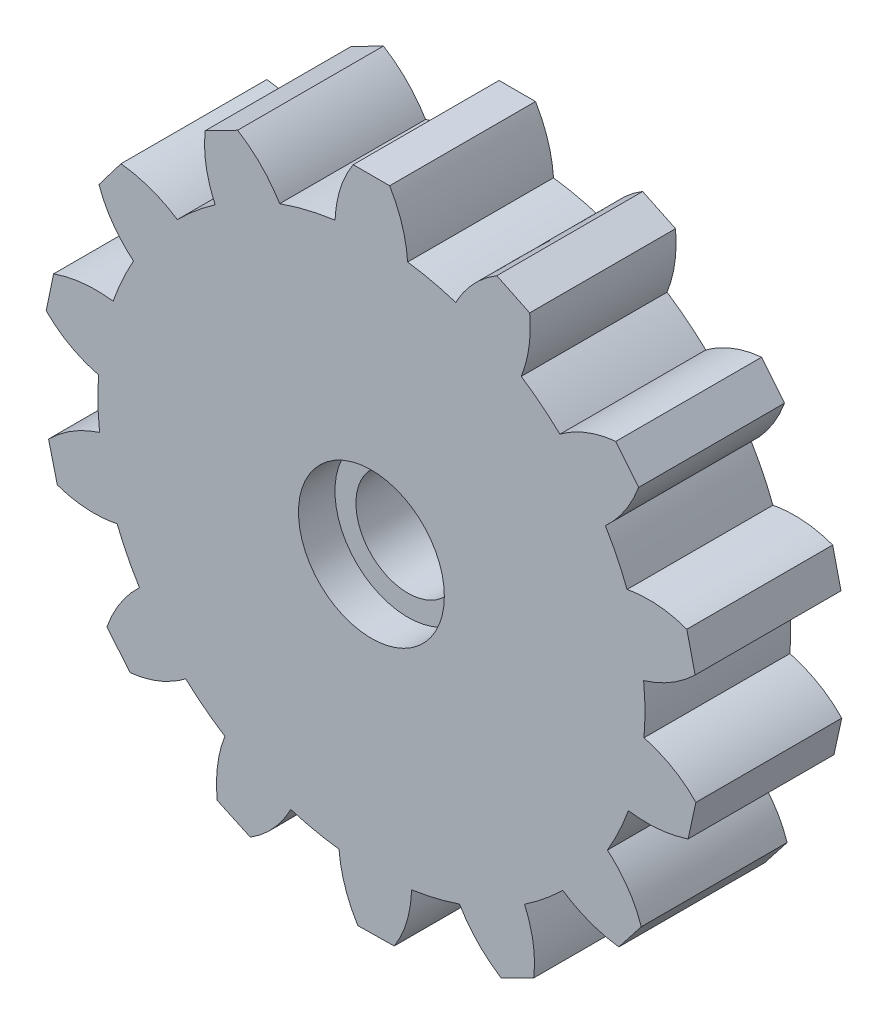
SolidWorks part; units mm, degrees
ref_plane "Front Plane" through (0, 0, 0) normal (0, 0, 1) x (1, 0, 0)
ref_plane "Top Plane" through (0, 0, 0) normal (0, 1, 0) x (1, 0, 0)
ref_plane "Right Plane" through (0, 0, 0) normal (1, 0, 0) x (0, 0, -1)
sketch "Sketch1" plane through (0, 0, 0) normal (0, 0, 1) x (1, 0, 0)
  line L1 (-1, 18) -> (1, 18)
  arc A0 (-1.9926, 14.8671) -> (1.9855, 14.868) centre (0, 0) ccw
  spline S0 degree 3 poles (1, 18) (1.5784, 17.0324) (1.9069, 15.9884) (1.9855, 14.868) knots 0 0 0 0 0.922232 0.922232 0.922232 0.922232
  spline S1 degree 3 poles (-1, 18) (-1.6088, 17.08) (-1.9397, 16.0357) (-1.9926, 14.8671) knots 0 0 0 0 0.925627 0.925627 0.925627 0.925627
  point P8 (0, 18)
  dimension "D1" = 30
  dimension "D3" = 2
extrude "Boss-Extrude1" add sketch "Sketch1" along normal blind 8 contours A0 S0 L1 S1
pattern_circular "CirPattern1" count 14 every 25.6 about axis through (0, 0, 8) along (0, 0, -1) of "Boss-Extrude1"
sketch "Sketch2" plane through (0, 0, 8) normal (0, 0, 1) x (1, 0, 0)
  circle A0 centre (0, 0) radius 2.85
  circle A1 centre (0, 0) radius 4
  dimension "D1" = 5.7
sketch "Sketch3" plane through (0, 0, 8) normal (0, 0, 1) x (1, 0, 0)
  circle A1 centre (0, 0) radius 4
extrude "Cut-Extrude2" cut sketch "Sketch3" against normal blind 2
extrude "Cut-Extrude4" cut sketch "Sketch2" against normal blind 14 contours A0
